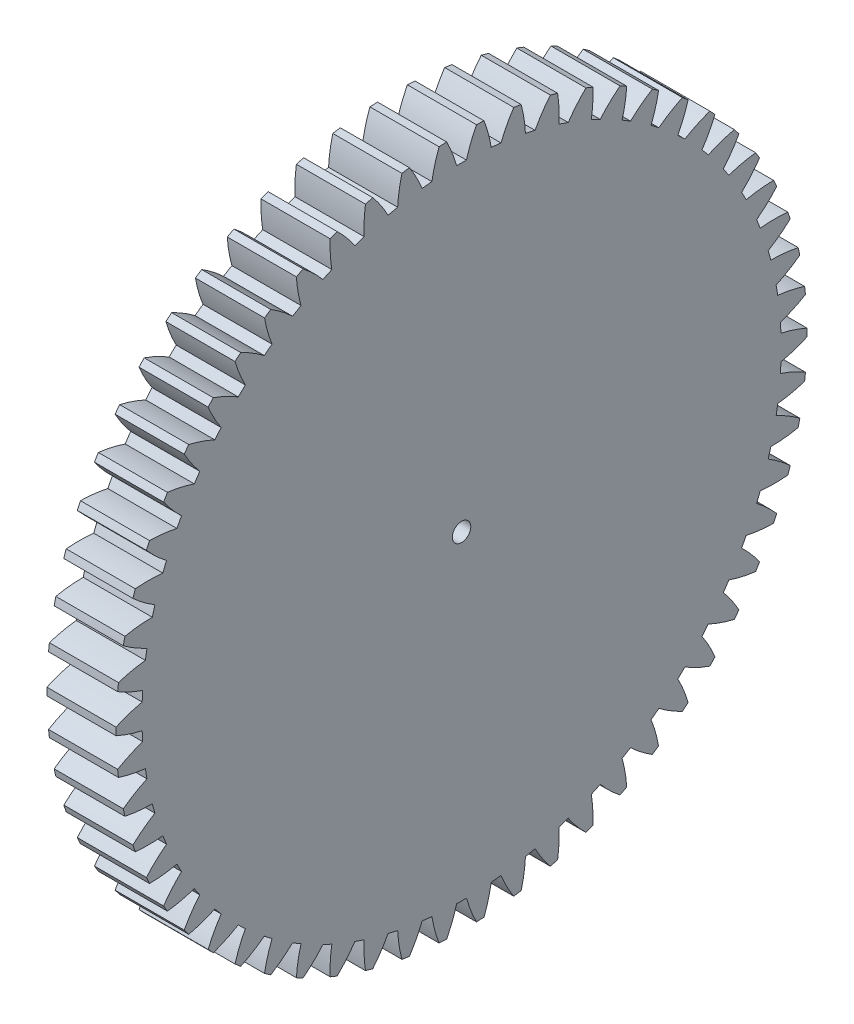
SolidWorks part; units mm, degrees
ref_plane "Plane1" through (0, 0, 0) normal (0, 0, 1) x (1, 0, 0)
ref_plane "Plane2" through (0, 0, 0) normal (0, 1, 0) x (1, 0, 0)
ref_plane "Plane3" through (0, 0, 0) normal (1, 0, 0) x (0, 0, -1)
sketch "HoldingSke" plane through (0, 0, 0) normal (0, 1, 0) x (1, 0, 0)
  line L0 (0, 0) -> (0.212, -0.3392)
  line L1 (-15, 0) -> (100, 0) construction
  line L2 (0, 0) -> (-2.1039, 2.3779)
  line L3 (0, 0) -> (-11.863, 4.5341)
  line L4 (0, 0) -> (4.5764, 7.3237)
  line L5 (0, 0) -> (-46.8476, -17.4728)
  line L6 (0, 0) -> (-12.4344, -8.3896)
  line L7 (-2.1039, 2.3779) -> (8.6586, 51.2059)
  line L8 (-76.2, 54.61) -> (-75.5, 54.61)
  line L9 (-71.009, 38.7566) -> (-53.1078, 45.2721)
  line L10 (-76.2, 71.12) -> (104.1128, 71.12)
  line L11 (0, 0) -> (-15, 0)
  line L12 (-76.2, 101.6) -> (-76.113, 101.6)
  line L13 (24.9733, 27.94) -> (52.9518, 28.4284)
  line L14 (24.9733, 27.94) -> (24.9743, 27.94)
  line L15 (24.9733, 27.94) -> (100.4006, 29.5858)
  line L16 (-63.627, -2.5) -> (-12.827, -2.5)
  circle A0 centre (0, 0) radius 2
  circle A1 centre (0, 0) radius 37.5
  circle A2 centre (0, 0) radius 37.5
  circle A3 centre (0, 0) radius 2
  dimension "MHD" = 75
  dimension "Hub_dia" = 75
  dimension "Bore" = 4
  dimension "MBD" = 4
  dimension "Num_teeth" = 58
  dimension "Pitch" = 0.4
  dimension "Overall_len" = 50
  dimension "Show_teeth" = 58
  dimension "Thickness" = 15
  dimension "OAL" = 50.0001
  dimension "T_dim" = 0.7
  dimension "Ap" = 20
  dimension "H" = 19.05
  dimension "Pitch_radius" = 180.3128
  dimension "Width" = 15
  dimension "Backlash" = 0.087
  dimension "Addendum_fac" = 1
  dimension "Dedendum_fac" = 1.25
  dimension "Clearance_fac" = 0.25
  dimension "Dedendum_add" = 0.001
  dimension "Module" = 2.5
sketch "BasProSke" plane through (0, 0, 0) normal (0, 1, 0) x (1, 0, 0)
  line L0 (-10, 0) -> (60, 0) construction
  line L1 (0, 0) -> (0, 75)
  line L2 (0, 0) -> (15, 0)
  line L3 (15, 0) -> (15, 75)
  line L4 (15, 75) -> (0, 75)
  dimension "Thickness" = 15
  dimension "Diameter" = 150
revolve "Base-Revolve" add sketch "BasProSke" angle 360 about L0
sketch "TooCutSke" plane through (0, 0, 0) normal (1, 0, 0) x (0, 0, -1)
  line L1 (0, 0) -> (0, 107) construction
  line L2 (0, 0) -> (-2.1155, 72.4691) construction
  line L3 (0, 0) -> (-7.8477, 144.7422) construction
  line L4 (-2.1155, 72.4691) -> (-3.9238, 72.3711) construction
  arc A0 (1.0657, 69.3658) -> (-1.0657, 69.3658) centre (0, 0) ccw
  arc A1 (3.2551, 74.9548) -> (-3.2551, 74.9548) centre (0, 0) ccw
  circle A2 centre (0, 0) radius 72.5 construction
  circle A3 centre (0, 0) radius 68.1277 construction
  arc A4 (-1.0657, 69.3658) -> (-3.2551, 74.9548) centre (-29.0174, 61.6391) ccw
  arc A5 (3.2551, 74.9548) -> (1.0657, 69.3658) centre (29.0174, 61.6391) ccw
  dimension "Root_dia" = 138.748
  dimension "Overcut_dia" = 150.0508
  dimension "Pitch_dia" = 145
  dimension "Base_dia" = 136.2554
  dimension "Flank_rad" = 29
  dimension "Half_ang" = 3.103
  dimension "Half_CT" = 1.811
extrude "ToothCut" cut sketch "TooCutSke" along normal through all
fillet "Breaks" [suppressed] radius 0.05
fillet "RootFillets" [suppressed] radius 0.626
pattern_circular "TeethCuts" count 58 every 6.207 about axis through (-10, 0, 0) along (1, 0, 0) of "ToothCut", "RootFillets", "Breaks"
sketch "HubNeaOneSke" plane through (0, 0, 0) normal (-1, 0, 0) x (0, 0, 1)
  circle A0 centre (0, 0) radius 37.5
  dimension "Diameter" = 75
extrude "HubNearOne" [suppressed] add sketch "HubNeaOneSke" along normal blind 35.0001
sketch "HubNeaBotSke" plane through (0, 0, 0) normal (-1, 0, 0) x (0, 0, 1)
  circle A0 centre (0, 0) radius 37.5
  dimension "Diameter" = 75
extrude "HubNearBoth" [suppressed] add sketch "HubNeaBotSke" along normal blind 17.5
ref_plane "FarPln" through (15, 0, 0) normal (1, 0, 0) x (0, 0, -1)
sketch "HubFarSke" plane through (15, 0, 0) normal (1, 0, 0) x (0, 0, -1)
  circle A0 centre (0, 0) radius 37.5
  dimension "Diameter" = 75
extrude "HubFar" [suppressed] add sketch "HubFarSke" along normal blind 17.5
sketch "BorSke" plane through (0, 0, 0) normal (1, 0, 0) x (0, 0, -1)
  circle A0 centre (0, 0) radius 2
  dimension "Diameter" = 4
extrude "Bore" cut sketch "BorSke" along normal mid plane 100.0001
sketch "KeySke" plane through (0, 0, 0) normal (1, 0, 0) x (0, 0, -1)
  line L0 (-0.8, 0) -> (-0.8, 2.7)
  line L1 (-0.8, 2.7) -> (0.8, 2.7)
  line L2 (0.8, 2.7) -> (0.8, 0)
  line L3 (0, 0) -> (0, 34) construction
  line L4 (-0.8, 0) -> (0.8, 0)
  dimension "Offset" = 2.7
  dimension "Width" = 1.6
extrude "Keyway" [suppressed] cut sketch "KeySke" along normal mid plane 100.0001
pattern_circular "Keyway2" [suppressed] count 2 every 90 about axis through (-10, 0, 0) along (1, 0, 0)
equation "' \"Module@HoldingSke\" = 6.35"
equation "' \"Num_teeth@HoldingSke\" = 12"
equation "' \"Ap@HoldingSke\" =  20"
equation "' \"Ap@HoldingSke\" = 20"
equation "' \"Width@HoldingSke\" = 0.5 * 25.4"
equation "' \"Hub_dia@HoldingSke\"= 1 * 25.4"
equation "' \"Hub_dia@HoldingSke\" = 1 * 25.4"
equation "' \"Overall_len@HoldingSke\" = 1.0 * 25.4"
equation "' \"Bore@HoldingSke\" = 0.75 * 25.4"
equation "' \"T_dim@HoldingSke\" = 0.1 * 25.4"
equation "' \"Width@KeySke\" = 0.25 * 25.4"
equation "' \"Show_teeth@HoldingSke\" = 13"
equation "' \"Backlash@HoldingSke\" = 0.009 * 25.4"
equation "' \"Addendum_fac@HoldingSke\" = 1.0"
equation "' \"Dedendum_fac@HoldingSke\" = 1.25"
equation "' \"Dedendum_add@HoldingSke\" = 0.00005 * 25.4"
equation "' \"Clearance_fac@HoldingSke\" = 0.25"
equation "\"Pitch@HoldingSke\" = 1 / \"Module@HoldingSke\""
equation "\"Overcut_dia@TooCutSke\" = (\"Num_teeth@HoldingSke\" + 2 * \"Addendum_fac@HoldingSke\") / \"Pitch@HoldingSke\" + 0.002 * 25.4"
equation "\"Pitch_dia@TooCutSke\" = \"Num_teeth@HoldingSke\" / \"Pitch@HoldingSke\""
equation "\"Base_dia@TooCutSke\" = \"Num_teeth@HoldingSke\" / \"Pitch@HoldingSke\" * cos((\"Ap@HoldingSke\"  * 3.14159265 / 180))"
equation "\"Root_dia@TooCutSke\" = (\"Num_teeth@HoldingSke\" + 2) / \"Pitch@HoldingSke\" - 2 * (\"Addendum_fac@HoldingSke\" + \"Dedendum_fac@HoldingSke\") / \"Pitch@HoldingSke\" - \"Dedendum_add@HoldingSke\" * 2"
equation "\"Half_ang@TooCutSke\" = 180 / \"Num_teeth@HoldingSke\""
equation "\"Half_CT@TooCutSke\" = \"Num_teeth@HoldingSke\" / \"Pitch@HoldingSke\" * sin((3.14159265 / 2 / \"Num_teeth@HoldingSke\")) / 2 - 7 * \"Backlash@HoldingSke\" / 4"
equation "\"Flank_rad@TooCutSke\" = \"Num_teeth@HoldingSke\" / \"Pitch@HoldingSke\" / 5"
equation "\"Radius@RootFillets\" = \"Clearance_fac@HoldingSke\" / \"Pitch@HoldingSke\" + \"Dedendum_add@HoldingSke\""
equation "\"Break_rad@Breaks\" = 0.02 / \"Pitch@HoldingSke\""
equation "\"Thickness@HoldingSke\" = \"Width@HoldingSke\""
equation "\"OAL@HoldingSke\" = \"Thickness@HoldingSke\""
equation "\"MHD@HoldingSke\" = (\"Num_teeth@HoldingSke\" + 2) / \"Pitch@HoldingSke\" - 2 * (\"Addendum_fac@HoldingSke\" + \"Dedendum_fac@HoldingSke\")  / \"Pitch@HoldingSke\" - \"Dedendum_add@HoldingSke\" * 2"
equation "\"MBD@HoldingSke\" = (\"Num_teeth@HoldingSke\" + 2) / \"Pitch@HoldingSke\" - 2 * (\"Addendum_fac@HoldingSke\" + \"Dedendum_fac@HoldingSke\")  / \"Pitch@HoldingSke\" - \"Dedendum_add@HoldingSke\" * 2 - 0.002 * 25.4"
equation "\"MHD@HoldingSke\" = ((sgn( \"MHD@HoldingSke\" - \"Hub_dia@HoldingSke\" )-1)*( \"MHD@HoldingSke\" - \"Hub_dia@HoldingSke\" ))/-2+ \"Hub_dia@HoldingSke\""
equation "\"MBD@HoldingSke\" = ((sgn( \"MBD@HoldingSke\" - \"Bore@HoldingSke\" )-1)*( \"MBD@HoldingSke\" - \"Bore@HoldingSke\" ))/-2+ \"Bore@HoldingSke\""
equation "\"OAL@HoldingSke\" = ((sgn( \"OAL@HoldingSke\" - \"Overall_len@HoldingSke\" )+1)*( \"OAL@HoldingSke\" - \"Overall_len@HoldingSke\" ))/2 + \"Overall_len@HoldingSke\" + 0.000002 * 25.4"
equation "\"Num_teeth@TeethCuts\" = int( \"Show_teeth@HoldingSke\" ) + 1"
equation "\"Num_teeth@TeethCuts\" = ((sgn( \"Num_teeth@TeethCuts\" - \"Num_teeth@HoldingSke\" )-1)*( \"Num_teeth@TeethCuts\" - \"Num_teeth@HoldingSke\" ))/-2+ \"Num_teeth@HoldingSke\""
equation "\"Num_teeth@TeethCuts\" = ((sgn( \"Num_teeth@TeethCuts\" - 2.0)+1)*( \"Num_teeth@TeethCuts\" - 2.0))/2 +2.0"
equation "\"Angle@TeethCuts\" = 360.0 / \"Num_teeth@HoldingSke\""
equation "\"Diameter@BasProSke\" = (\"Num_teeth@HoldingSke\" + 2 * \"Addendum_fac@HoldingSke\") / \"Pitch@HoldingSke\""
equation "\"Thickness@BasProSke\"  = \"Thickness@HoldingSke\""
equation "' \"Fillet_rad@BasProSke\" =  \"Thickness@HoldingSke\" * 0.05"
equation "' \"Fillet_rad@BasProSke\" = \"Thickness@HoldingSke\" * 0.05"
equation "\"MHD@HoldingSke\" = ((sgn( \"MHD@HoldingSke\" - \"Root_dia@TooCutSke\" )-1)*( \"MHD@HoldingSke\" - \"Root_dia@TooCutSke\" ))/-2+ \"Root_dia@TooCutSke\""
equation "\"Diameter@HubNeaOneSke\" = \"MHD@HoldingSke\""
equation "\"Length@HubNearOne\" = \"OAL@HoldingSke\" - \"Thickness@BasProSke\""
equation "\"Diameter@HubNeaBotSke\" = \"MHD@HoldingSke\""
equation "\"Length@HubNearBoth\" = ( \"OAL@HoldingSke\" - \"Thickness@BasProSke\" ) / 2.0"
equation "\"Thickness@FarPln\" = \"Thickness@BasProSke\""
equation "\"Diameter@HubFarSke\" = \"MHD@HoldingSke\""
equation "\"Length@HubFar\" = ( \"OAL@HoldingSke\" - \"Thickness@BasProSke\" ) / 2.0"
equation "\"Diameter@BorSke\" = \"MBD@HoldingSke\""
equation "\"D1@Bore\" = \"OAL@HoldingSke\" * 2.0"
equation "\"D1@Keyway\" = \"OAL@HoldingSke\" * 2.0"
equation "\"Offset@KeySke\" = \"T_dim@HoldingSke\" + \"MBD@HoldingSke\" / 2.0"
